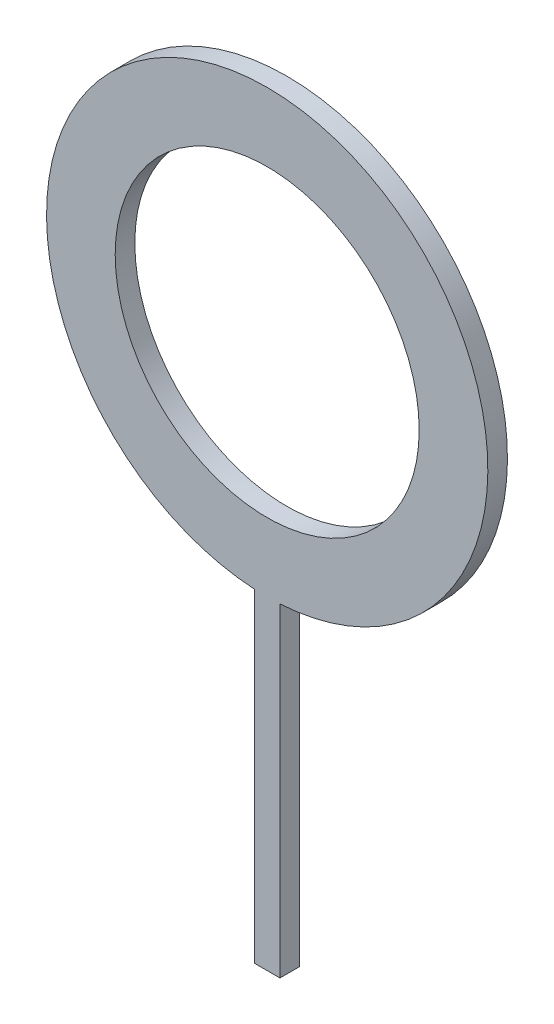
SolidWorks part; units mm, degrees
ref_plane "Front" through (0, 0, 0) normal (0, 0, 1) x (1, 0, 0)
ref_plane "Top" through (0, 0, 0) normal (0, 1, 0) x (1, 0, 0)
ref_plane "Right" through (0, 0, 0) normal (1, 0, 0) x (0, 0, -1)
sketch "Sketch1" plane through (0, 0, 0) normal (0, 0, 1) x (1, 0, 0)
  line L0 (0, -7.75) -> (0, -27.75)
  line L2 (-0.65, -27.75) -> (0.65, -27.75)
  line L3 (-0.65, -27.75) -> (-0.65, -7.75)
  line L4 (-0.65, -7.75) -> (0.65, -7.75)
  line L5 (0.65, -27.75) -> (0.65, -7.75)
  circle A0 centre (0, 0) radius 11.25
  circle A1 centre (0, 0) radius 7.75
  point P10 (0, -7.75)
  point P11 (0, 0)
  point P12 (0, -2.0905)
  point P13 (0, -27.75)
  point P14 (0, 0)
  dimension "D1" = 22.5
  dimension "D2" = 15.5
  dimension "D3" = 1.3
  dimension "D4" = 20
extrude "Boss-Extrude1" add sketch "Sketch1" along normal blind 1 contours L4 A1 L5 A0 L3 | L0 A0 L5 L4 | L3 A0 L0 L4 | A0 L3 L2 L0 | A0 L0 L2 L5
